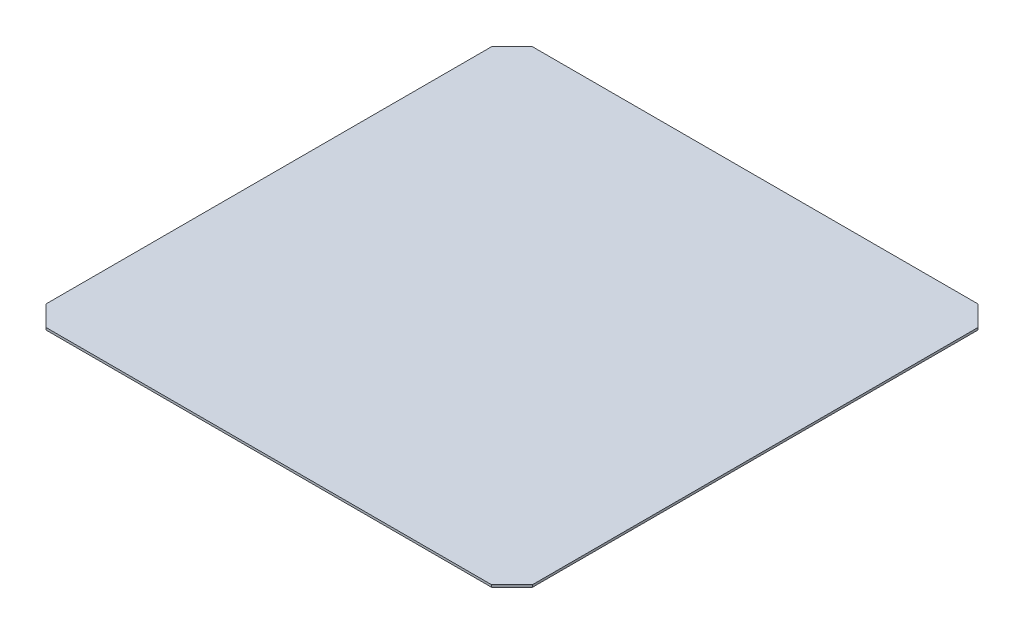
SolidWorks part; units mm, degrees
ref_plane "Front Plane" through (0, 0, 0) normal (0, 0, 1) x (1, 0, 0)
ref_plane "Top Plane" through (0, 0, 0) normal (0, 1, 0) x (1, 0, 0)
ref_plane "Right Plane" through (0, 0, 0) normal (1, 0, 0) x (0, 0, -1)
sketch "Sketch1" plane through (0, 158.9735, 0) normal (0, 1, 0) x (1, 0, 0)
  line L0 (127.9362, -354.1186) -> (191.9362, -354.1186)
  line L1 (-11.0638, -139.1186) -> (191.9362, -139.1186)
  line L2 (-17.0638, -145.1186) -> (-17.0638, -348.1186)
  line L3 (-11.0638, -354.1186) -> (52.9362, -354.1186)
  line L4 (197.9362, -145.1186) -> (197.9362, -348.1186)
  line L9 (-17.0638, -139.1186) -> (197.9362, -139.1186) construction
  line L18 (-11.0638, -139.1186) -> (-17.0638, -139.1186)
  line L27 (-17.0638, -139.1186) -> (-17.0638, -145.1186)
  line L28 (191.9362, -139.1186) -> (197.9362, -139.1186)
  line L29 (197.9362, -139.1186) -> (197.9362, -145.1186)
  line L30 (-17.0638, -348.1186) -> (-17.0638, -354.1186)
  line L31 (-17.0638, -354.1186) -> (-11.0638, -354.1186)
  line L32 (191.9362, -354.1186) -> (197.9362, -354.1186)
  line L33 (197.9362, -354.1186) -> (197.9362, -348.1186)
  line L34 (52.9362, -354.1186) -> (127.9362, -354.1186)
  dimension "D8" = 0
extrude "Boss-Extrude1" add sketch "Sketch1" along normal blind 1
chamfer "Chamfer2" distance 9 angle 45 4 edges at (-17.0638, 159.4735, 139.1186) (197.9362, 159.4735, 139.1186) (197.9362, 159.4735, 354.1186) (-17.0638, 159.4735, 354.1186)
